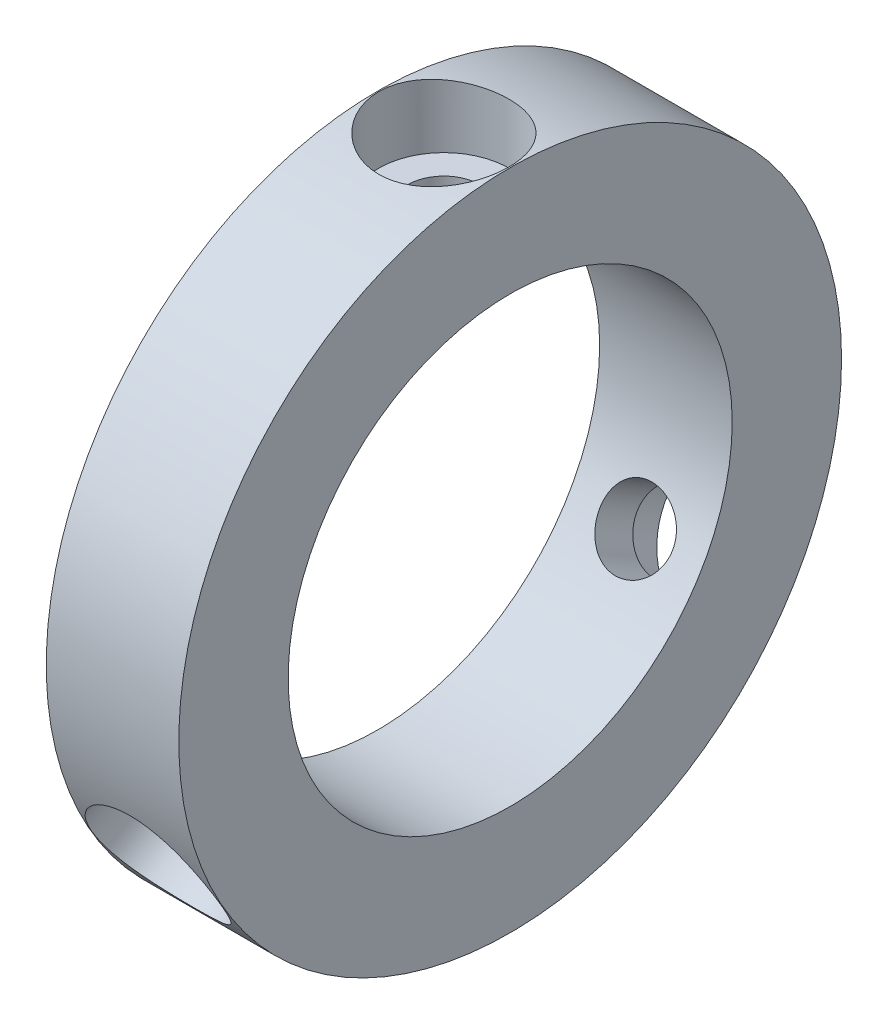
SolidWorks part; units mm, degrees
ref_plane "Front Plane" through (0, 0, 0) normal (0, 0, 1) x (1, 0, 0)
ref_plane "Top Plane" through (0, 0, 0) normal (0, 1, 0) x (1, 0, 0)
ref_plane "Right Plane" through (0, 0, 0) normal (1, 0, 0) x (0, 0, -1)
sketch "Sketch1" plane through (0, 0, 0) normal (1, 0, 0) x (0, 0, -1)
  circle A0 centre (0, 0) radius 10.05
  circle A1 centre (0, 0) radius 15
  dimension "D1" = 20.1
  dimension "D2" = 30
extrude "Boss-Extrude1" add sketch "Sketch1" along normal blind 6
sketch "Sketch2" plane through (6, 0, 0) normal (1, 0, 0) x (0, 0, -1)
  line L0 (0, 0) -> (0, 15) construction
  line L1 (0, 0) -> (12.9904, -7.5) construction
  line L2 (0, 0) -> (-12.9904, -7.5) construction
  circle A0 centre (0, 0) radius 15 construction
  dimension "D1" = 120
  dimension "D2" = 120
ref_plane "Plane1" through (0, -7.5, 12.9904) normal (0, -0.5, 0.866) x (1, 0, 0)
sketch "Sketch3" plane through (0, -7.5, 12.9904) normal (0, -0.5, 0.866) x (1, 0, 0)
  circle A0 centre (3, 0) radius 2.95
  dimension "D1" = 5.9
  dimension "D2" = 3
extrude "Cut-Extrude1" cut sketch "Sketch3" against normal blind 3
pattern_circular "CirPattern1" count 3 over 360 about axis through (0, 0, 0) along (1, 0, 0) of "Cut-Extrude1"
sketch "Sketch4" plane through (0, -7.5, 12.9904) normal (0, -0.5, 0.866) x (1, 0, 0)
  circle A0 centre (3, 0) radius 1.65
  dimension "D1" = 3.3
extrude "Cut-Extrude2" cut sketch "Sketch4" against normal blind 11
pattern_circular "CirPattern3" count 3 over 360 about axis through (6, 0, 0) along (-1, 0, 0) of "Cut-Extrude2"
